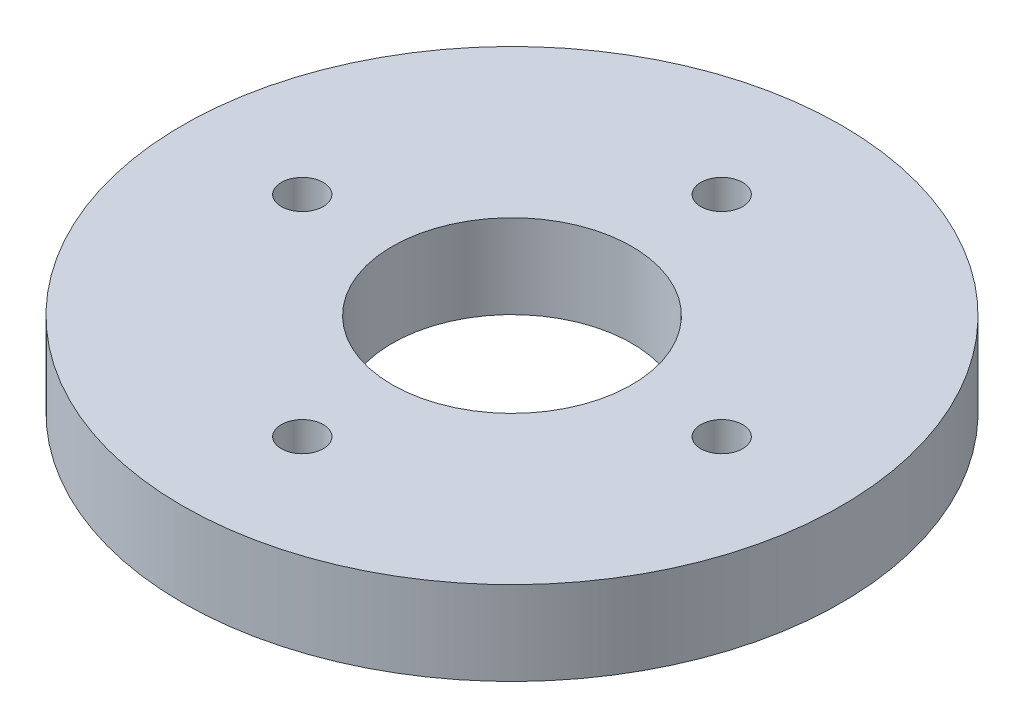
SolidWorks part; units mm, degrees
ref_plane "Front Plane" through (0, 0, 0) normal (0, 0, 1) x (1, 0, 0)
ref_plane "Top Plane" through (0, 0, 0) normal (0, 1, 0) x (1, 0, 0)
ref_plane "Right Plane" through (0, 0, 0) normal (1, 0, 0) x (0, 0, -1)
other "Configuration Table"
sketch "草图1" plane through (0, 0, 0) normal (0, 1, 0) x (1, 0, 0)
  line L0 (-15.4, 0) -> (15.4, 0) construction
  line L1 (0, -15.4) -> (0, 15.4) construction
  circle A0 centre (0, 0) radius 110
  circle A1 centre (0, 0) radius 40
  circle A2 centre (70, 0) radius 7
  circle A3 centre (-70, 0) radius 7
  circle A4 centre (0, 70) radius 7
  circle A5 centre (0, -70) radius 7
extrude "凸台-拉伸1" add sketch "草图1" along normal blind 28
